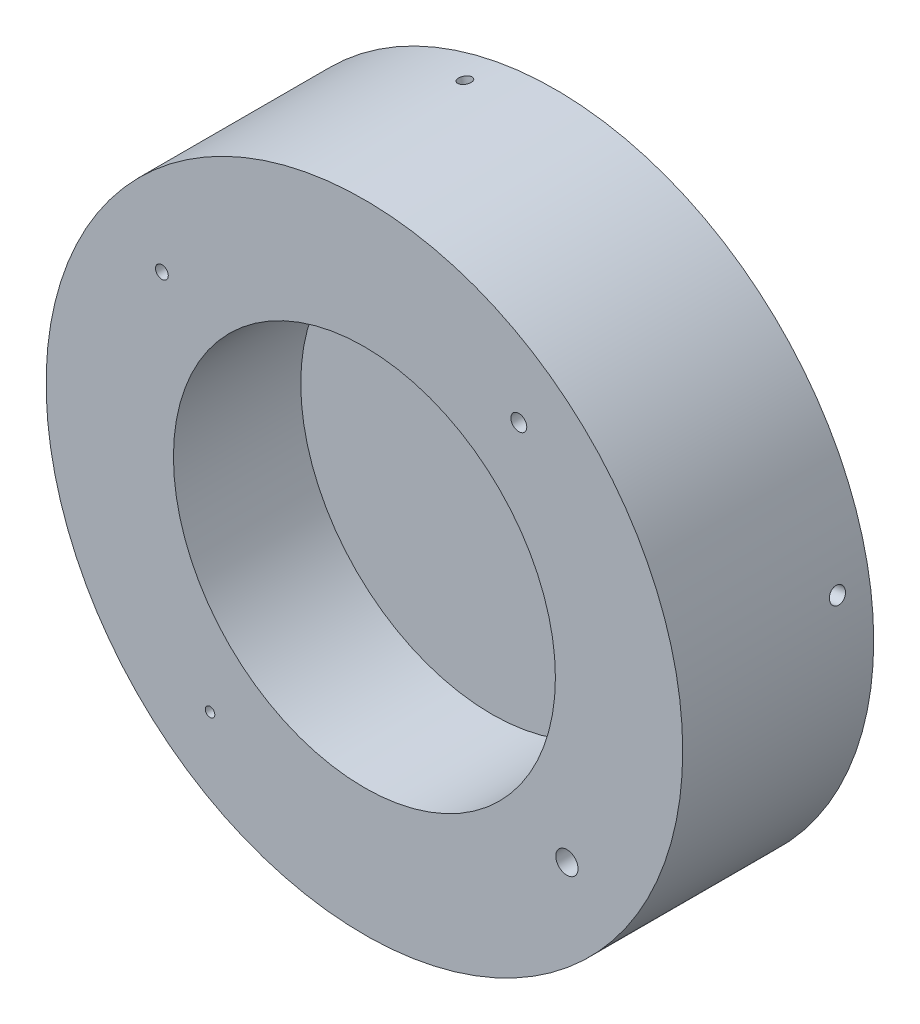
SolidWorks part; units mm, degrees
ref_plane "Ebene vorne" through (0, 0, 0) normal (0, 0, 1) x (1, 0, 0)
ref_plane "Ebene oben" through (0, 0, 0) normal (0, 1, 0) x (1, 0, 0)
ref_plane "Ebene rechts" through (0, 0, 0) normal (1, 0, 0) x (0, 0, -1)
sketch "Skizze1" plane through (0, 0, 0) normal (0, 0, 1) x (1, 0, 0)
  circle A0 centre (0, 0) radius 50
  dimension "D1" = 100
extrude "Aufsatz-Linear austragen1" add sketch "Skizze1" along normal blind 30
sketch "Skizze2" plane through (0, 0, 30) normal (0, 0, 1) x (1, 0, 0)
  circle A0 centre (0, 0) radius 30
  dimension "D1" = 60
extrude "Schnitt-Linear austragen1" cut sketch "Skizze2" against normal blind 20
hole_wizard "Ø3.5 (3.5) Durchmesser Bohrung1" positions "3D-Skizze6" profile "Skizze6" hole size "Ø3.5" standard "DIN"
sketch3d "3D-Skizze6"
  circle A3 centre (0, 0, 0) radius 50 construction
  point P2 (9.7642, -49.0373, 5)
  point P17 (0, 0, 50)
  dimension "D1" = 50.2494
  dimension "D2" = 0
sketch "Skizze6" plane through (9.7642, -49.0373, 5) normal (0, 0, 1) x (0.9807, 0.1953, 0)
  line L0 (0, 0) -> (0, 41.0515)
  line L1 (0, 41.0515) -> (1.75, 40)
  line L2 (1.75, 40) -> (1.75, 0)
  line L5 (1.75, 0) -> (0, 0)
  line L10 (0, 41.0515) -> (-1.75, 40) construction
  line L11 (0, -6.35) -> (0, 107.95) construction
  dimension "Bohrerdurchmesser" = 3.5
  dimension "Bohrungstiefe" = 40
  dimension "Spitzenwinkel" = 118
hole_wizard "Ø2.5 (2.5) Durchmesser Bohrung1" positions "3D-Skizze7" profile "Skizze7" hole size "Ø2.5" standard "DIN"
sketch3d "3D-Skizze7"
  line L0 (8.3359, -49.3002, 4.0234) -> (49.3018, 8.3265, 5) construction
  circle A0 centre (0, 0, 0) radius 50 construction
  spline S1 degree 3 poles (11.4745, -48.6655, 5.2312) (11.4745, -48.6655, 4.8844) (11.4635, -48.6681, 4.7707) (11.4202, -48.6783, 4.547) (11.3874, -48.686, 4.4359) (11.3018, -48.706, 4.224) (11.2494, -48.7181, 4.1234) (11.1256, -48.7465, 3.9332) (11.0535, -48.763, 3.8432) (10.8172, -48.8161, 3.601) (10.6265, -48.8582, 3.4706) (10.2146, -48.946, 3.2961) (9.989, -48.9926, 3.2501) (9.6532, -49.0594, 3.2499) (9.5394, -49.0817, 3.2613) (9.319, -49.124, 3.3059) (9.2118, -49.1442, 3.339) (9.0034, -49.1828, 3.4266) (8.9026, -49.2012, 3.4814) (8.7158, -49.2346, 3.608) (8.6288, -49.2499, 3.6803) (8.4677, -49.2778, 3.8436) (8.3961, -49.29, 3.9321) (8.2711, -49.3112, 4.1216) (8.217, -49.3202, 4.2238) (8.1302, -49.3346, 4.4359) (8.0976, -49.3399, 4.545) (8.0533, -49.3472, 4.7692) (8.042, -49.349, 4.8852) (8.0418, -49.349, 5.2278) (8.0871, -49.3417, 5.458) (8.259, -49.3132, 5.8793) (8.3876, -49.2917, 6.0747) (8.6259, -49.2504, 6.317) (8.7144, -49.2348, 6.3909) (8.9018, -49.2013, 6.5182) (9.0006, -49.1833, 6.572) (9.2087, -49.1448, 6.66) (9.3181, -49.1242, 6.6938) (9.5378, -49.082, 6.7385) (9.6493, -49.0602, 6.7499) (9.9889, -48.9926, 6.7502) (10.2114, -48.9466, 6.705) (10.5228, -48.8803, 6.5734) (10.6212, -48.859, 6.5197) (10.807, -48.8182, 6.393) (10.895, -48.7986, 6.3191) (11.1317, -48.7454, 6.077) (11.2588, -48.716, 5.882) (11.4293, -48.6763, 5.461) (11.4745, -48.6655, 5.2312) (11.4745, -48.6655, 4.8844) (11.4635, -48.6681, 4.7707) knots -0.0625 -0.0625 0 0 0.03125 0.03125 0.0625 0.0625 0.09375 0.09375 0.125 0.125 0.1875 0.1875 0.25 0.25 0.28125 0.28125 0.3125 0.3125 0.34375 0.34375 0.375 0.375 0.40625 0.40625 0.4375 0.4375 0.46875 0.46875 0.5 0.5 0.5625 0.5625 0.625 0.625 0.65625 0.65625 0.6875 0.6875 0.71875 0.71875 0.75 0.75 0.8125 0.8125 0.84375 0.84375 0.875 0.875 0.9375 0.9375 1 1 1.03125 1.03125 1.0625 only from (11.4745, -48.6655, 5) to (11.4745, -48.6655, 5) construction
  point P0 (49.3018, 8.3265, 5)
  point P7 (0, 0, 50)
  dimension "D1" = 50.2494
  dimension "D3" = 70.7107
sketch "Skizze7" plane through (49.3018, 8.3265, 5) normal (0, 0, 1) x (-0.1665, 0.986, 0)
  line L0 (0, 0) -> (0, 40.7511)
  line L1 (0, 40.7511) -> (1.25, 40)
  line L2 (1.25, 40) -> (1.25, 0)
  line L5 (1.25, 0) -> (0, 0)
  line L10 (0, 40.7511) -> (-1.25, 40) construction
  line L11 (0, -6.35) -> (0, 107.95) construction
  dimension "Bohrerdurchmesser" = 2.5
  dimension "Bohrungstiefe" = 40
  dimension "Spitzenwinkel" = 118
hole_wizard "Ø2.0 (2) Durchmesser Bohrung1" positions "3D-Skizze8" profile "Skizze8" hole size "Ø2.0" standard "DIN"
sketch3d "3D-Skizze8"
  line L0 (49.1409, 9.2291, 5.8497) -> (-9.222, 49.1422, 5) construction
  line L2 (-9.222, 49.1422, 5) -> (8.4732, -49.2768, 6.157) construction
  circle A0 centre (0, 0, 0) radius 50 construction
  spline S0 degree 3 poles (49.0782, 9.5565, 5.1652) (49.0782, 9.5565, 4.8348) (49.0845, 9.5245, 4.6728) (49.1082, 9.4013, 4.37) (49.1257, 9.31, 4.2313) (49.1682, 9.0833, 4.0007) (49.1934, 8.9461, 3.9076) (49.2463, 8.65, 3.7829) (49.2746, 8.4879, 3.7501) (49.3289, 8.1664, 3.7499) (49.3553, 8.0047, 3.7823) (49.4029, 7.7058, 3.9074) (49.4238, 7.5696, 3.9991) (49.4586, 7.3387, 4.2323) (49.4719, 7.2478, 4.3699) (49.4855, 7.1546, 4.5971) (49.4889, 7.1312, 4.675) (49.4934, 7.0995, 4.8351) (49.4946, 7.0914, 4.918) (49.4946, 7.0913, 5.1627) (49.49, 7.1237, 5.3271) (49.4721, 7.2468, 5.6281) (49.4586, 7.3389, 5.7677) (49.4243, 7.5667, 5.9984) (49.4032, 7.7039, 6.0915) (49.3557, 8.0024, 6.2171) (49.3295, 8.1627, 6.2498) (49.2746, 8.4878, 6.2502) (49.2467, 8.6477, 6.2179) (49.2067, 8.8716, 6.1238) (49.1939, 8.9423, 6.0855) (49.1694, 9.076, 5.995) (49.1577, 9.1393, 5.9422) (49.1258, 9.3096, 5.7693) (49.1083, 9.4011, 5.63) (49.0846, 9.5239, 5.3292) (49.0782, 9.5565, 5.1652) (49.0782, 9.5565, 4.8348) (49.0845, 9.5245, 4.6728) knots -0.0625 -0.0625 0 0 0.0625 0.0625 0.125 0.125 0.1875 0.1875 0.25 0.25 0.3125 0.3125 0.375 0.375 0.4375 0.4375 0.46875 0.46875 0.5 0.5 0.5625 0.5625 0.625 0.625 0.6875 0.6875 0.75 0.75 0.8125 0.8125 0.84375 0.84375 0.875 0.875 0.9375 0.9375 1 1 1.0625 1.0625 1.125 only from (49.0782, 9.5565, 5) to (49.0782, 9.5565, 5) construction
  spline S1 degree 3 poles (11.4745, -48.6655, 5.2312) (11.4745, -48.6655, 4.8844) (11.4635, -48.6681, 4.7707) (11.4202, -48.6783, 4.547) (11.3874, -48.686, 4.4359) (11.3018, -48.706, 4.224) (11.2494, -48.7181, 4.1234) (11.1256, -48.7465, 3.9332) (11.0535, -48.763, 3.8432) (10.8172, -48.8161, 3.601) (10.6265, -48.8582, 3.4706) (10.2146, -48.946, 3.2961) (9.989, -48.9926, 3.2501) (9.6532, -49.0594, 3.2499) (9.5394, -49.0817, 3.2613) (9.319, -49.124, 3.3059) (9.2118, -49.1442, 3.339) (9.0034, -49.1828, 3.4266) (8.9026, -49.2012, 3.4814) (8.7158, -49.2346, 3.608) (8.6288, -49.2499, 3.6803) (8.4677, -49.2778, 3.8436) (8.3961, -49.29, 3.9321) (8.2711, -49.3112, 4.1216) (8.217, -49.3202, 4.2238) (8.1302, -49.3346, 4.4359) (8.0976, -49.3399, 4.545) (8.0533, -49.3472, 4.7692) (8.042, -49.349, 4.8852) (8.0418, -49.349, 5.2278) (8.0871, -49.3417, 5.458) (8.259, -49.3132, 5.8793) (8.3876, -49.2917, 6.0747) (8.6259, -49.2504, 6.317) (8.7144, -49.2348, 6.3909) (8.9018, -49.2013, 6.5182) (9.0006, -49.1833, 6.572) (9.2087, -49.1448, 6.66) (9.3181, -49.1242, 6.6938) (9.5378, -49.082, 6.7385) (9.6493, -49.0602, 6.7499) (9.9889, -48.9926, 6.7502) (10.2114, -48.9466, 6.705) (10.5228, -48.8803, 6.5734) (10.6212, -48.859, 6.5197) (10.807, -48.8182, 6.393) (10.895, -48.7986, 6.3191) (11.1317, -48.7454, 6.077) (11.2588, -48.716, 5.882) (11.4293, -48.6763, 5.461) (11.4745, -48.6655, 5.2312) (11.4745, -48.6655, 4.8844) (11.4635, -48.6681, 4.7707) knots -0.0625 -0.0625 0 0 0.03125 0.03125 0.0625 0.0625 0.09375 0.09375 0.125 0.125 0.1875 0.1875 0.25 0.25 0.28125 0.28125 0.3125 0.3125 0.34375 0.34375 0.375 0.375 0.40625 0.40625 0.4375 0.4375 0.46875 0.46875 0.5 0.5 0.5625 0.5625 0.625 0.625 0.65625 0.65625 0.6875 0.6875 0.71875 0.71875 0.75 0.75 0.8125 0.8125 0.84375 0.84375 0.875 0.875 0.9375 0.9375 1 1 1.03125 1.03125 1.0625 only from (11.4745, -48.6655, 5) to (11.4745, -48.6655, 5) construction
  point P0 (-9.222, 49.1422, 5)
  point P9 (0, 0, 50)
  dimension "D2" = 50.2494
  dimension "D1" = 70.7107
  dimension "D3" = 100.0038
sketch "Skizze8" plane through (-9.222, 49.1422, 5) normal (0, 0, 1) x (-0.9828, -0.1844, 0)
  line L0 (0, 0) -> (0, 40.6009)
  line L1 (0, 40.6009) -> (1, 40)
  line L2 (1, 40) -> (1, 0)
  line L5 (1, 0) -> (0, 0)
  line L10 (0, 40.6009) -> (-1, 40) construction
  line L11 (0, -6.35) -> (0, 107.95) construction
  dimension "Bohrerdurchmesser" = 2
  dimension "Bohrungstiefe" = 40
  dimension "Spitzenwinkel" = 118
hole_wizard "Ø1.5 (1.5) Durchmesser Bohrung1" positions "3D-Skizze9" profile "Skizze9" hole size "Ø1.5" standard "DIN"
sketch3d "3D-Skizze9"
  line L0 (-10.1528, 48.9584, 5.3137) -> (-48.9586, -10.1518, 5) construction
  line L1 (-48.9586, -10.1518, 5) -> (10.1231, -48.9645, 6.7113) construction
  circle A0 centre (0, 0, 0) radius 50 construction
  spline S0 degree 3 poles (-10.203, 48.9479, 5.2643) (-10.203, 48.9479, 4.8679) (-10.1775, 48.9533, 4.7382) (-10.0792, 48.9736, 4.496) (-10.0064, 48.9886, 4.3851) (-9.8255, 49.0252, 4.2006) (-9.7161, 49.047, 4.1261) (-9.4799, 49.0932, 4.0263) (-9.3507, 49.118, 4.0001) (-9.0943, 49.1662, 3.9999) (-8.9654, 49.1898, 4.0258) (-8.727, 49.2326, 4.1259) (-8.6185, 49.2517, 4.1992) (-8.4344, 49.2836, 4.3858) (-8.362, 49.2958, 4.4959) (-8.2629, 49.3125, 4.7383) (-8.2373, 49.3168, 4.8691) (-8.2372, 49.3168, 5.1302) (-8.263, 49.3125, 5.2617) (-8.3612, 49.296, 5.5025) (-8.4346, 49.2835, 5.6141) (-8.6162, 49.2521, 5.7987) (-8.7255, 49.2329, 5.8732) (-8.9635, 49.1901, 5.9737) (-9.0913, 49.1667, 5.9999) (-9.3506, 49.1181, 6.0001) (-9.4781, 49.0936, 5.9743) (-9.7162, 49.047, 5.874) (-9.8249, 49.0253, 5.7999) (-10.0966, 48.9703, 5.5232) (-10.203, 48.9479, 5.2643) (-10.203, 48.9479, 4.8679) (-10.1775, 48.9533, 4.7382) knots -0.125 -0.125 0 0 0.0625 0.0625 0.125 0.125 0.1875 0.1875 0.25 0.25 0.3125 0.3125 0.375 0.375 0.4375 0.4375 0.5 0.5 0.5625 0.5625 0.625 0.625 0.6875 0.6875 0.75 0.75 0.8125 0.8125 0.875 0.875 1 1 1.0625 1.0625 1.125 only from (-10.203, 48.9479, 5) to (-10.203, 48.9479, 5) construction
  spline S1 degree 3 poles (11.4745, -48.6655, 5.2312) (11.4745, -48.6655, 4.8844) (11.4635, -48.6681, 4.7707) (11.4202, -48.6783, 4.547) (11.3874, -48.686, 4.4359) (11.3018, -48.706, 4.224) (11.2494, -48.7181, 4.1234) (11.1256, -48.7465, 3.9332) (11.0535, -48.763, 3.8432) (10.8172, -48.8161, 3.601) (10.6265, -48.8582, 3.4706) (10.2146, -48.946, 3.2961) (9.989, -48.9926, 3.2501) (9.6532, -49.0594, 3.2499) (9.5394, -49.0817, 3.2613) (9.319, -49.124, 3.3059) (9.2118, -49.1442, 3.339) (9.0034, -49.1828, 3.4266) (8.9026, -49.2012, 3.4814) (8.7158, -49.2346, 3.608) (8.6288, -49.2499, 3.6803) (8.4677, -49.2778, 3.8436) (8.3961, -49.29, 3.9321) (8.2711, -49.3112, 4.1216) (8.217, -49.3202, 4.2238) (8.1302, -49.3346, 4.4359) (8.0976, -49.3399, 4.545) (8.0533, -49.3472, 4.7692) (8.042, -49.349, 4.8852) (8.0418, -49.349, 5.2278) (8.0871, -49.3417, 5.458) (8.259, -49.3132, 5.8793) (8.3876, -49.2917, 6.0747) (8.6259, -49.2504, 6.317) (8.7144, -49.2348, 6.3909) (8.9018, -49.2013, 6.5182) (9.0006, -49.1833, 6.572) (9.2087, -49.1448, 6.66) (9.3181, -49.1242, 6.6938) (9.5378, -49.082, 6.7385) (9.6493, -49.0602, 6.7499) (9.9889, -48.9926, 6.7502) (10.2114, -48.9466, 6.705) (10.5228, -48.8803, 6.5734) (10.6212, -48.859, 6.5197) (10.807, -48.8182, 6.393) (10.895, -48.7986, 6.3191) (11.1317, -48.7454, 6.077) (11.2588, -48.716, 5.882) (11.4293, -48.6763, 5.461) (11.4745, -48.6655, 5.2312) (11.4745, -48.6655, 4.8844) (11.4635, -48.6681, 4.7707) knots -0.0625 -0.0625 0 0 0.03125 0.03125 0.0625 0.0625 0.09375 0.09375 0.125 0.125 0.1875 0.1875 0.25 0.25 0.28125 0.28125 0.3125 0.3125 0.34375 0.34375 0.375 0.375 0.40625 0.40625 0.4375 0.4375 0.46875 0.46875 0.5 0.5 0.5625 0.5625 0.625 0.625 0.65625 0.65625 0.6875 0.6875 0.71875 0.71875 0.75 0.75 0.8125 0.8125 0.84375 0.84375 0.875 0.875 0.9375 0.9375 1 1 1.03125 1.03125 1.0625 only from (11.4745, -48.6655, 5) to (11.4745, -48.6655, 5) construction
  point P0 (-48.9586, -10.1518, 5)
  point P5 (0, 0, 50)
  dimension "D1" = 50.2494
  dimension "D2" = 70.7107
  dimension "D3" = 70.7107
  dimension "D4" = 90.011
sketch "Skizze9" plane through (-48.9586, -10.1518, 5) normal (0, 0, 1) x (0.203, -0.9792, 0)
  line L0 (0, 0) -> (0, 40.4506)
  line L1 (0, 40.4506) -> (0.75, 40)
  line L2 (0.75, 40) -> (0.75, 0)
  line L5 (0.75, 0) -> (0, 0)
  line L10 (0, 40.4506) -> (-0.75, 40) construction
  line L11 (0, -6.35) -> (0, 107.95) construction
  dimension "Bohrerdurchmesser" = 1.5
  dimension "Bohrungstiefe" = 40
  dimension "Spitzenwinkel" = 118
hole_wizard "Ø3.5 (3.5) Durchmesser Bohrung2" positions "Skizze10" profile "Skizze12" hole size "Ø3.5" standard "DIN" end condition through all
sketch "Skizze10" plane through (0, 0, 30) normal (0, 0, 1) x (1, 0, 0)
  line L0 (5.8585, -29.4224) -> (9.7642, -49.0373) construction
  line L2 (-39.2731, -58.8016) -> (58.8016, -39.2731) construction
  circle A0 centre (0, 0) radius 30 construction
  circle A1 centre (0, 0) radius 50 construction
  circle A2 centre (0, 0) radius 40
  point P30 (31.8066, -24.2557)
  dimension "D3" = 80
  dimension "D4" = 90
  dimension "D1" = 0
  dimension "D2" = 90
sketch "Skizze12" plane through (31.8066, -24.2557, 30) normal (1, 0, 0) x (0, -1, 0)
  line L0 (0, 0) -> (0, 30)
  line L1 (0, 30) -> (1.75, 30)
  line L2 (1.75, 30) -> (1.75, 0)
  line L5 (1.75, 0) -> (0, 0)
  line L11 (0, -6.35) -> (0, 107.95) construction
  dimension "Bohrerdurchmesser" = 3.5
  dimension "Bohrungstiefe" = 30
hole_wizard "Ø2.5 (2.5) Durchmesser Bohrung2" positions "Skizze13" profile "Skizze14" hole size "Ø2.5" standard "DIN" end condition through all
sketch "Skizze13" plane through (0, 0, 30) normal (0, 0, 1) x (1, 0, 0)
  circle A1 centre (0, 0) radius 30 construction
  circle A3 centre (31.8066, -24.2557) radius 1.75 construction
  point P0 (24.254, 31.8079)
  dimension "D1" = 56.57
  dimension "D2" = 40
sketch "Skizze14" plane through (24.254, 31.8079, 30) normal (1, 0, 0) x (0, -1, 0)
  line L0 (0, 0) -> (0, 30)
  line L1 (0, 30) -> (1.25, 30)
  line L2 (1.25, 30) -> (1.25, 0)
  line L5 (1.25, 0) -> (0, 0)
  line L11 (0, -6.35) -> (0, 107.95) construction
  dimension "Bohrerdurchmesser" = 2.5
  dimension "Bohrungstiefe" = 30
hole_wizard "Ø2.0 (2) Durchmesser Bohrung2" positions "Skizze15" profile "Skizze16" hole size "Ø2.0" standard "DIN" end condition through all
sketch "Skizze15" plane through (0, 0, 30) normal (0, 0, 1) x (1, 0, 0)
  circle A3 centre (24.254, 31.8079) radius 1.25 construction
  point P0 (-31.8091, 24.2524)
  dimension "D1" = 40
  dimension "D2" = 56.57
sketch "Skizze16" plane through (-31.8091, 24.2524, 30) normal (1, 0, 0) x (0, -1, 0)
  line L0 (0, 0) -> (0, 30)
  line L1 (0, 30) -> (1, 30)
  line L2 (1, 30) -> (1, 0)
  line L5 (1, 0) -> (0, 0)
  line L11 (0, -6.35) -> (0, 107.95) construction
  dimension "Bohrerdurchmesser" = 2
  dimension "Bohrungstiefe" = 30
hole_wizard "Ø1.5 (1.5) Durchmesser Bohrung3" positions "Skizze17" profile "Skizze18" hole size "Ø1.5" standard "DIN" end condition through all
sketch "Skizze17" plane through (0, 0, 30) normal (0, 0, 1) x (1, 0, 0)
  circle A9 centre (-31.8091, 24.2524) radius 1 construction
  point P0 (-24.2507, -31.8104)
  dimension "D1" = 56.57
  dimension "D2" = 40
sketch "Skizze18" plane through (-24.2507, -31.8104, 30) normal (1, 0, 0) x (0, -1, 0)
  line L0 (0, 0) -> (0, 30)
  line L1 (0, 30) -> (0.75, 30)
  line L2 (0.75, 30) -> (0.75, 0)
  line L5 (0.75, 0) -> (0, 0)
  line L11 (0, -6.35) -> (0, 107.95) construction
  dimension "Bohrerdurchmesser" = 1.5
  dimension "Bohrungstiefe" = 30
